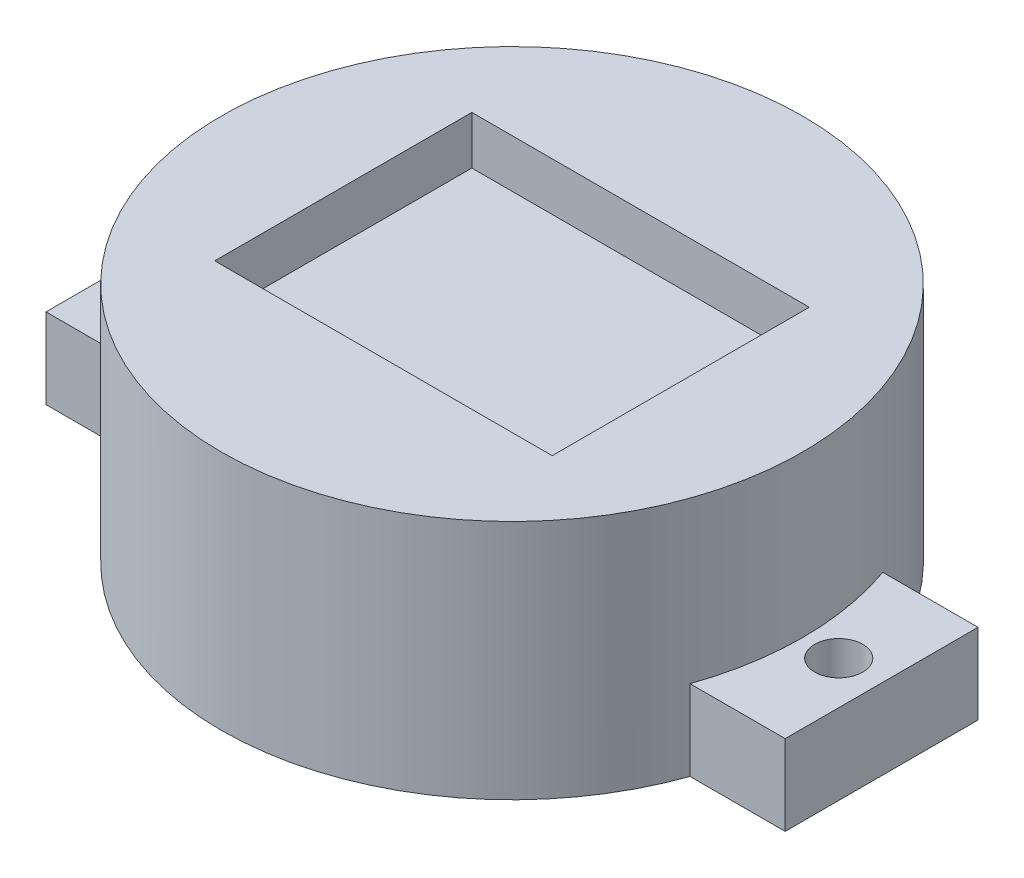
SolidWorks part; units mm, degrees
ref_plane "Alzado" through (0, 0, 0) normal (0, 0, 1) x (1, 0, 0)
ref_plane "Planta" through (0, 0, 0) normal (0, 1, 0) x (1, 0, 0)
ref_plane "Vista lateral" through (0, 0, 0) normal (1, 0, 0) x (0, 0, -1)
sketch "Croquis1" plane through (0, 0, 0) normal (0, 0, 1) x (1, 0, 0)
  line L0 (0, 25.323) -> (0, -26.2274) construction
  line L1 (-18.1, 9) -> (-18.1, -6)
  line L2 (-18.1, -6) -> (-13.1, -6)
  line L3 (-13.1, -6) -> (-13.1, 0)
  line L4 (-13.1, 0) -> (0, 0)
  line L5 (-18.1, 9) -> (0, 9)
  line L6 (0, 9) -> (0, 0)
  dimension "D1" = 13.1
  dimension "D2" = 5
  dimension "D3" = 15
  dimension "D4" = 6
revolve "Revolución1" add sketch "Croquis1" angle 360 about L0
sketch "Croquis2" plane through (0, 9, 0) normal (0, 1, 0) x (1, 0, 0)
  line L1 (-10.5, -8) -> (10.5, -8)
  line L2 (-10.5, -8) -> (-10.5, 8)
  line L3 (-10.5, 8) -> (10.5, 8)
  line L4 (10.5, -8) -> (10.5, 8)
  line L5 (-10.5, -8) -> (10.5, 8) construction
  line L6 (-10.5, 8) -> (10.5, -8) construction
  point P0 (0, 0)
  dimension "D1" = 21
  dimension "D2" = 16
extrude "Cortar-Extruir1" cut sketch "Croquis2" against normal blind 3
hole_wizard "Taladro de margen para #31" positions "Croquis3D1" profile "Croquis3" hole size "#3" standard "Ansi Inch"
sketch3d "Croquis3D1"
  point P0 (-8.6259, 15.6699, 32.6334)
  point P4 (5.6794, 15.6699, 27.9228)
sketch "Croquis3" plane through (-8.6259, 15.6699, 32.6334) normal (1, 0, 0) x (0, 0, 1)
  line L0 (0, 0) -> (0, 10.8394)
  line L1 (0, 10.8394) -> (1.397, 10)
  line L2 (1.397, 10) -> (1.397, 0)
  line L3 (1.397, 0) -> (0, 0)
  line L4 (0, 10.8394) -> (-1.397, 10) construction
  line L5 (0, -6.35) -> (0, 107.95) construction
  dimension "Diámetro de taladro" = 2.794
  dimension "Profundidad de taladro" = 10
  dimension "Ángulo de perforador" = 118
sketch "Croquis4" plane through (0, -6, 0) normal (0, -1, 0) x (1, 0, 0)
  line L0 (24.1305, 0) -> (-26.9261, 0) construction
  line L1 (-15, 6) -> (-23, 6)
  line L2 (-15, 6) -> (-15, -6)
  line L3 (-15, -6) -> (-23, -6)
  line L4 (-23, 6) -> (-23, -6)
  line L5 (0, -20.6483) -> (0, 20.7169) construction
  line L6 (15, -6) -> (23, -6)
  line L7 (23, 6) -> (23, -6)
  line L8 (15, 6) -> (23, 6)
  line L9 (15, 6) -> (15, -6)
  circle A0 centre (-20.3333, 0) radius 1.5
  circle A1 centre (20.3333, 0) radius 1.5
  point P12 (0, 0)
  dimension "D4" = 3
  dimension "D1" = 12
  dimension "D2" = 23
  dimension "D3" = 8
  dimension "D5" = 5.3333
extrude "Saliente-Extruir1" add sketch "Croquis4" against normal blind 5
